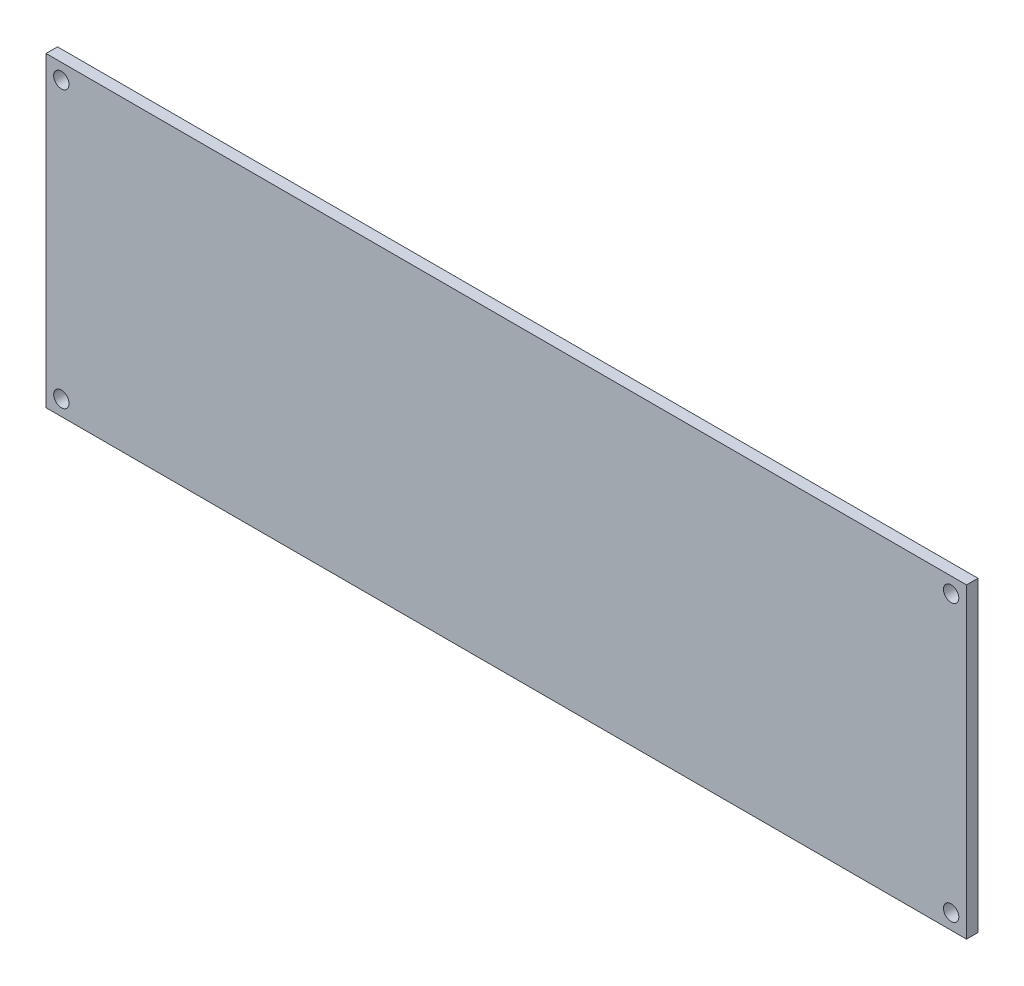
SolidWorks part; units mm, degrees
ref_plane "Спереди" through (0, 0, 0) normal (0, 0, 1) x (1, 0, 0)
ref_plane "Сверху" through (0, 0, 0) normal (0, 1, 0) x (1, 0, 0)
ref_plane "Справа" through (0, 0, 0) normal (1, 0, 0) x (0, 0, -1)
sketch "Эскиз1" plane through (0, 0, 0) normal (0, 0, 1) x (1, 0, 0)
  line L1 (0, 0) -> (120, 0)
  line L2 (0, 0) -> (0, 40)
  line L3 (0, 40) -> (120, 40)
  line L4 (120, 0) -> (120, 40)
  line L5 (60, 0) -> (60, 40) construction
  line L6 (60, 40) -> (60, 20) construction
  line L7 (120, 20) -> (0, 20) construction
  circle A0 centre (2, 38) radius 1
  circle A1 centre (118, 38) radius 1
  circle A2 centre (118, 2) radius 1
  circle A3 centre (2, 2) radius 1
  dimension "D3" = 2
  dimension "D1" = 120
  dimension "D2" = 40
  dimension "D4" = 2
  dimension "D5" = 2
extrude "Бобышка-Вытянуть1" add sketch "Эскиз1" along normal blind 1.5
